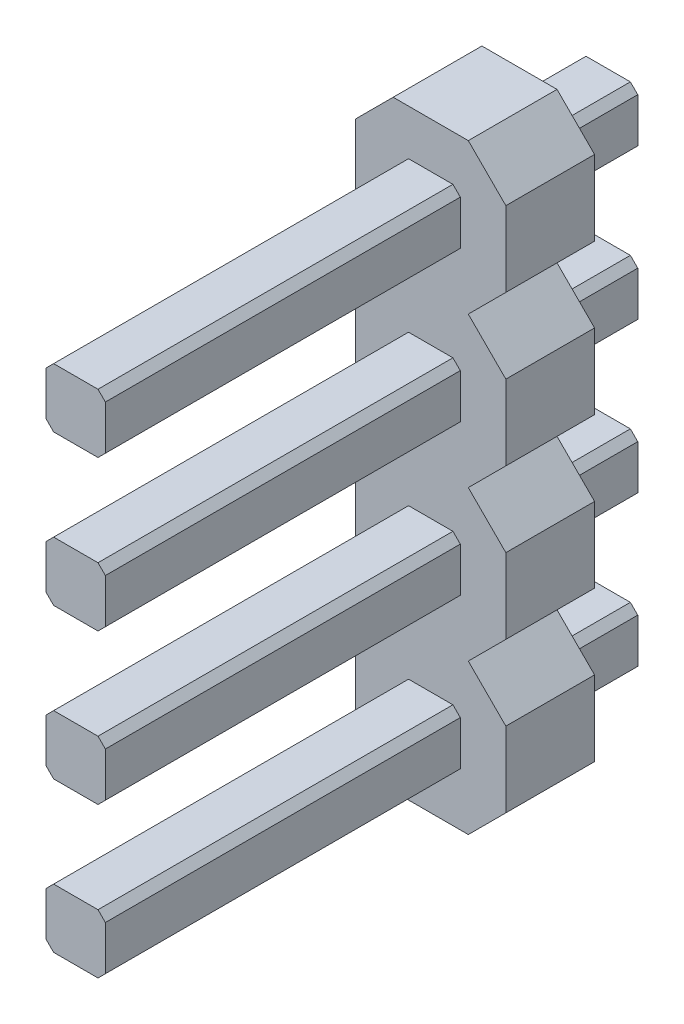
SolidWorks part; units mm, degrees
ref_plane "Plan de face" through (0, 0, 0) normal (0, 0, 1) x (1, 0, 0)
ref_plane "Plan de dessus" through (0, 0, 0) normal (0, 1, 0) x (1, 0, 0)
ref_plane "Plan de droite" through (0, 0, 0) normal (1, 0, 0) x (0, 0, -1)
sketch "Sketch1" plane through (0, 0, 0) normal (0, 0, 1) x (1, 0, 0)
  line L0 (-0.635, 10.16) -> (0.635, 10.16)
  line L1 (0.635, 10.16) -> (1.27, 9.525)
  line L2 (1.27, 9.525) -> (1.27, 8.255)
  line L3 (1.27, 8.255) -> (0.635, 7.62)
  line L4 (-0.635, 10.16) -> (-1.27, 9.525)
  line L5 (-1.27, 9.525) -> (-1.27, 8.255)
  line L6 (-1.27, 8.255) -> (-0.635, 7.62)
  line L7 (0.635, 7.62) -> (1.27, 6.985)
  line L8 (1.27, 6.985) -> (1.27, 5.715)
  line L9 (1.27, 5.715) -> (0.635, 5.08)
  line L10 (-0.635, 7.62) -> (-1.27, 6.985)
  line L11 (-1.27, 6.985) -> (-1.27, 5.715)
  line L12 (-1.27, 5.715) -> (-0.635, 5.08)
  line L13 (0.635, 5.08) -> (1.27, 4.445)
  line L14 (1.27, 4.445) -> (1.27, 3.175)
  line L15 (1.27, 3.175) -> (0.635, 2.54)
  line L16 (-0.635, 5.08) -> (-1.27, 4.445)
  line L17 (-1.27, 4.445) -> (-1.27, 3.175)
  line L18 (-1.27, 3.175) -> (-0.635, 2.54)
  line L19 (0.635, 2.54) -> (1.27, 1.905)
  line L20 (1.27, 1.905) -> (1.27, 0.635)
  line L21 (1.27, 0.635) -> (0.635, 0)
  line L22 (-0.635, 2.54) -> (-1.27, 1.905)
  line L23 (-1.27, 1.905) -> (-1.27, 0.635)
  line L24 (-1.27, 0.635) -> (-0.635, 0)
  line L50 (-0.635, 7.62) -> (0.635, 7.62) construction
  line L51 (0, 10.16) -> (0, 7.62) construction
  line L52 (-0.635, 0) -> (0.635, 0)
  point P0 (0, 8.89)
  point P1 (0, 8.89)
  point P54 (0, 8.89)
extrude "Boss-Extrude1" add sketch "Sketch1" along normal blind 1.5
sketch "Sketch2" plane through (0, 0, 1.5) normal (0, 0, 1) x (1, 0, 0)
  line L0 (-1.27, 8.89) -> (1.27, 8.89) construction
  line L1 (-1.27, 9.525) -> (-1.27, 8.255) construction
  line L2 (1.27, 8.255) -> (1.27, 9.525) construction
  line L3 (0.5, 9.265) -> (0.375, 9.39)
  line L4 (0.375, 9.39) -> (-0.375, 9.39)
  line L5 (0.5, 9.265) -> (0.5, 8.515)
  line L6 (0.375, 8.39) -> (-0.375, 8.39)
  line L7 (-0.5, 9.265) -> (-0.5, 8.515)
  line L8 (0.5, 9.39) -> (-0.5, 8.39) construction
  line L9 (0.5, 8.39) -> (-0.5, 9.39) construction
  line L10 (0.5, 8.515) -> (0.375, 8.39)
  line L11 (-0.375, 8.39) -> (-0.5, 8.515)
  line L12 (-0.375, 9.39) -> (-0.5, 9.265)
  line L13 (0.5, 6.725) -> (0.375, 6.85)
  line L14 (0.375, 6.85) -> (-0.375, 6.85)
  line L15 (0.5, 6.725) -> (0.5, 5.975)
  line L16 (0.375, 5.85) -> (-0.375, 5.85)
  line L17 (-0.5, 6.725) -> (-0.5, 5.975)
  line L18 (0.5, 5.975) -> (0.375, 5.85)
  line L19 (-0.375, 5.85) -> (-0.5, 5.975)
  line L20 (-0.375, 6.85) -> (-0.5, 6.725)
  line L21 (0.5, 6.85) -> (-0.5, 5.85) construction
  line L22 (0.5, 5.85) -> (-0.5, 6.85) construction
  line L23 (0.5, 4.185) -> (0.375, 4.31)
  line L24 (0.375, 4.31) -> (-0.375, 4.31)
  line L25 (0.5, 4.185) -> (0.5, 3.435)
  line L26 (0.375, 3.31) -> (-0.375, 3.31)
  line L27 (-0.5, 4.185) -> (-0.5, 3.435)
  line L28 (0.5, 3.435) -> (0.375, 3.31)
  line L29 (-0.375, 3.31) -> (-0.5, 3.435)
  line L30 (-0.375, 4.31) -> (-0.5, 4.185)
  line L31 (0.5, 4.31) -> (-0.5, 3.31) construction
  line L32 (0.5, 3.31) -> (-0.5, 4.31) construction
  line L33 (0.5, 1.645) -> (0.375, 1.77)
  line L34 (0.375, 1.77) -> (-0.375, 1.77)
  line L35 (0.5, 1.645) -> (0.5, 0.895)
  line L36 (0.375, 0.77) -> (-0.375, 0.77)
  line L37 (-0.5, 1.645) -> (-0.5, 0.895)
  line L38 (0.5, 0.895) -> (0.375, 0.77)
  line L39 (-0.375, 0.77) -> (-0.5, 0.895)
  line L40 (-0.375, 1.77) -> (-0.5, 1.645)
  line L41 (0.5, 1.77) -> (-0.5, 0.77) construction
  line L42 (0.5, 0.77) -> (-0.5, 1.77) construction
  point P6 (0, 8.89)
  point P20 (0, 6.35)
  point P33 (0, 3.81)
  point P46 (0, 1.27)
  dimension "D1" = 1
  dimension "D2" = 1
  dimension "D3" = 4
extrude "Boss-Extrude2" add sketch "Sketch2" along normal blind 6 and the other way blind 3
